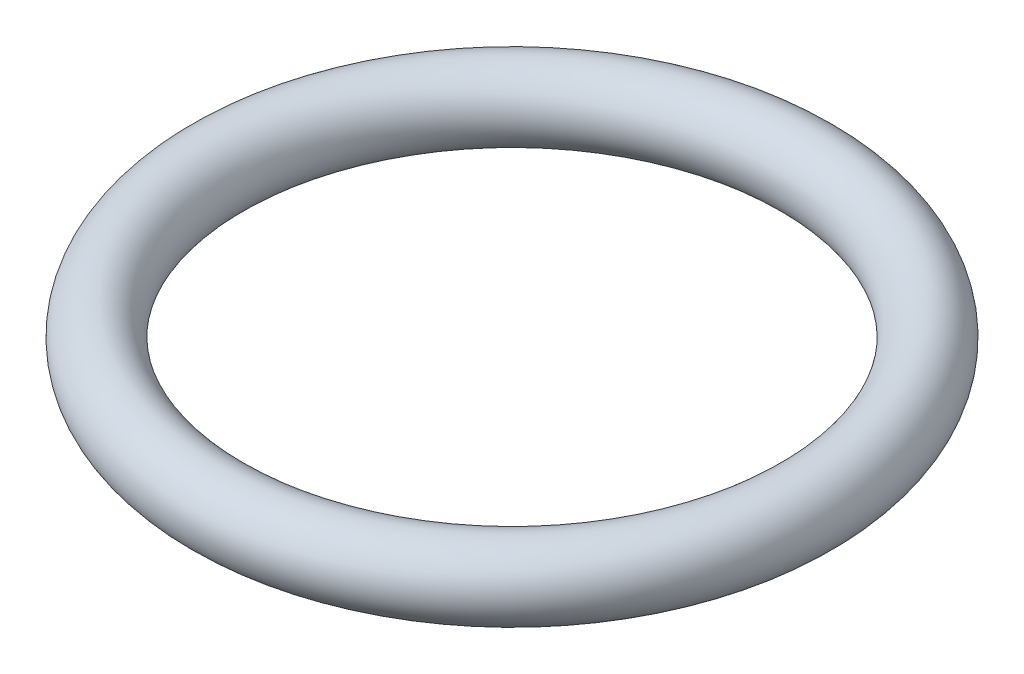
SolidWorks part; units mm, degrees
ref_plane "Front Plane" through (0, 0, 0) normal (0, 0, 1) x (1, 0, 0)
ref_plane "Top Plane" through (0, 0, 0) normal (0, 1, 0) x (1, 0, 0)
ref_plane "Right Plane" through (0, 0, 0) normal (1, 0, 0) x (0, 0, -1)
sketch "Sketch1" plane through (0, 0, 0) normal (0, 0, 1) x (1, 0, 0)
  line L0 (0, -3.9721) -> (0, 8.9728) construction
  circle A0 centre (-7, 0) radius 0.85
  dimension "D1" = 1.7
  dimension "D2" = 7
revolve "Revolve1" add sketch "Sketch1" angle 360 about L0
